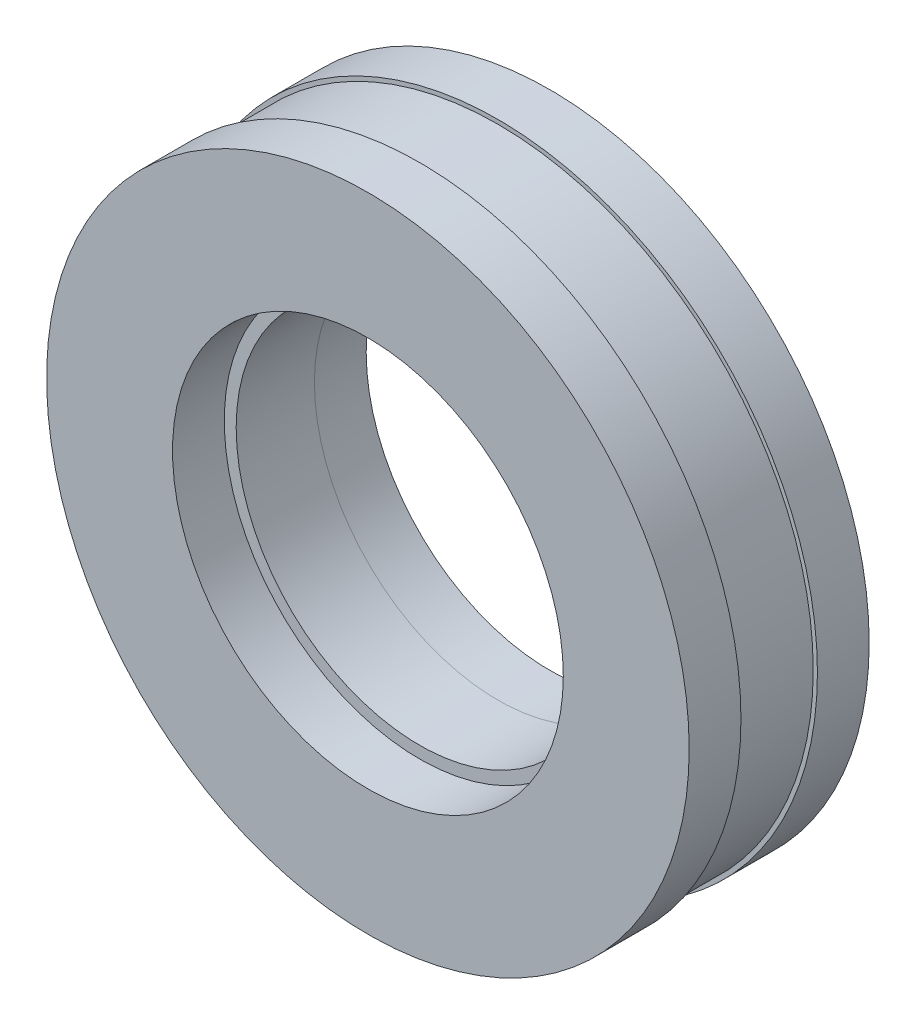
SolidWorks part; units mm, degrees
ref_plane "Front Plane" through (0, 0, 0) normal (0, 0, 1) x (1, 0, 0)
ref_plane "Top Plane" through (0, 0, 0) normal (0, 1, 0) x (1, 0, 0)
ref_plane "Right Plane" through (0, 0, 0) normal (1, 0, 0) x (0, 0, -1)
sketch "Sketch1" plane through (0, 0, 0) normal (0, 0, 1) x (1, 0, 0)
  circle A0 centre (0, 0) radius 17.399
  circle A1 centre (0, 0) radius 10
  dimension "D1" = 34.798
  dimension "D2" = 20
extrude "Boss-Extrude1" add sketch "Sketch1" along normal blind 2.8194
sketch "Sketch3" plane through (0, 0, 2.8194) normal (0, 0, 1) x (1, 0, 0)
  circle A0 centre (0, 0) radius 17.1704
  circle A2 centre (0, 0) radius 9.9949
  dimension "D1" = 34.3408
  dimension "D2" = 19.9898
extrude "Boss-Extrude2" add sketch "Sketch3" along normal blind 4.2672
sketch "Sketch4" plane through (0, 0, 7.0866) normal (0, 0, 1) x (1, 0, 0)
  circle A0 centre (0, 0) radius 17.5006
  circle A1 centre (0, 0) radius 10.6426
  dimension "D1" = 35.0012
  dimension "D2" = 21.2852
extrude "Boss-Extrude3" add sketch "Sketch4" along normal blind 2.8194
